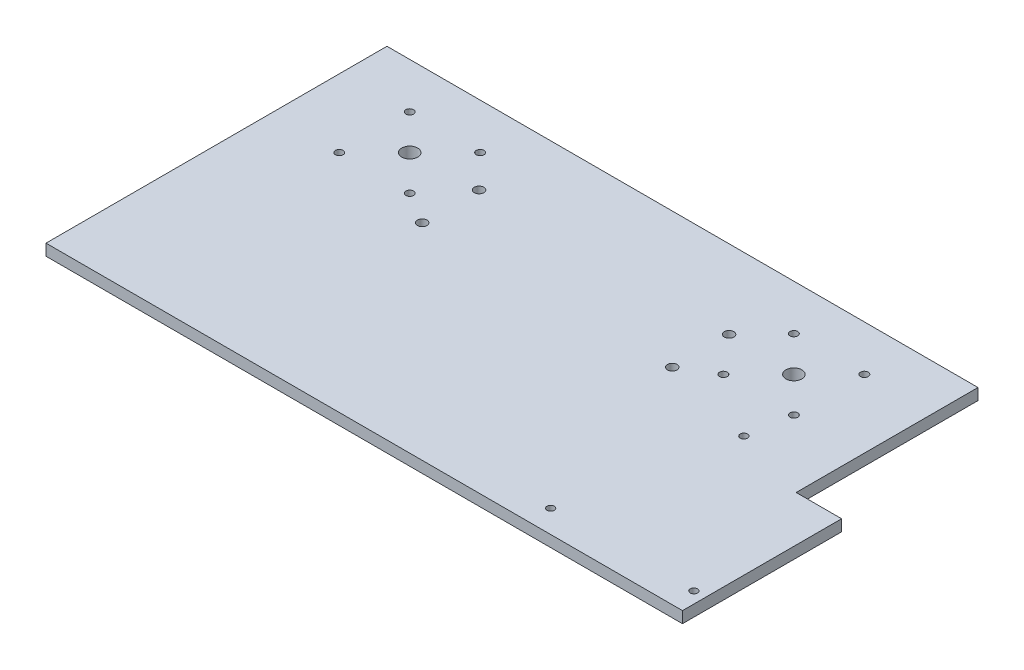
SolidWorks part; units mm, degrees
ref_plane "前视基准面" through (0, 0, 0) normal (0, 0, 1) x (1, 0, 0)
ref_plane "上视基准面" through (0, 0, 0) normal (0, 1, 0) x (1, 0, 0)
ref_plane "右视基准面" through (0, 0, 0) normal (1, 0, 0) x (0, 0, -1)
sketch "草图1" plane through (0, 0, 0) normal (0, 1, 0) x (1, 0, 0)
  line L1 (-140, -75) -> (140, -75)
  line L2 (-140, -75) -> (-140, 75)
  line L3 (-140, 75) -> (140, 75)
  line L4 (140, -75) -> (140, 75)
  line L5 (-140, -75) -> (140, 75) construction
  line L6 (-140, 75) -> (140, -75) construction
  line L7 (140, 75) -> (120, 75)
  line L8 (140, 75) -> (140, -5)
  line L9 (140, -5) -> (120, -5)
  line L10 (120, 75) -> (120, -5)
  line L11 (59, 24) -> (90, 24) construction
  line L12 (59, 24) -> (59, 55) construction
  line L13 (59, 55) -> (90, 55) construction
  line L14 (90, 24) -> (90, 55) construction
  line L15 (59, 24) -> (90, 55) construction
  line L16 (59, 55) -> (90, 24) construction
  line L17 (-110, 24) -> (-79, 24) construction
  line L18 (-110, 24) -> (-110, 55) construction
  line L19 (-110, 55) -> (-79, 55) construction
  line L20 (-79, 24) -> (-79, 55) construction
  line L21 (-110, 24) -> (-79, 55) construction
  line L22 (-110, 55) -> (-79, 24) construction
  line L24 (-65, 40.5) -> (45, 40.5) construction
  line L25 (-65, 40.5) -> (-65, 15.5) construction
  line L26 (-65, 15.5) -> (45, 15.5) construction
  line L27 (45, 40.5) -> (45, 15.5) construction
  circle A0 centre (59, 55) radius 1.7
  circle A1 centre (90, 55) radius 1.7
  circle A2 centre (59, 24) radius 1.7
  circle A3 centre (90, 24) radius 1.7
  circle A4 centre (-110, 55) radius 1.7
  circle A5 centre (-79, 55) radius 1.7
  circle A6 centre (-110, 24) radius 1.7
  circle A7 centre (-79, 24) radius 1.7
  circle A8 centre (-94.5, 39.5) radius 3.5
  circle A9 centre (74.5, 39.5) radius 3.5
  circle A10 centre (-65, 15.5) radius 2.1
  circle A11 centre (-65, 40.5) radius 2.1
  circle A12 centre (45, 15.5) radius 2.1
  circle A13 centre (45, 40.5) radius 2.1
  circle A17 centre (135, -65) radius 1.6
  circle A18 centre (87, 5) radius 1.6
  circle A19 centre (72, -65) radius 1.6
  point P0 (0, 0)
  point P9 (74.5, 39.5)
  dimension "D9" = 3.4
  dimension "D10" = 3.4
  dimension "D11" = 3.4
  dimension "D12" = 3.4
  dimension "D17" = 3.4
  dimension "D18" = 3.4
  dimension "D19" = 3.4
  dimension "D20" = 3.4
  dimension "D21" = 7
  dimension "D22" = 7
  dimension "D27" = 4.2
  dimension "D28" = 4.2
  dimension "D29" = 4.2
  dimension "D30" = 4.2
  dimension "D31" = 10
  dimension "D32" = 10
  dimension "D33" = 80
  dimension "D34" = 68
  dimension "D35" = 53
  dimension "D36" = 5
  dimension "D37" = 3.2
  dimension "D38" = 3.2
  dimension "D39" = 3.2
  dimension "D1" = 280
  dimension "D2" = 150
  dimension "D3" = 80
  dimension "D4" = 20
  dimension "D5" = 20
  dimension "D6" = 31
  dimension "D7" = 31
  dimension "D8" = 50
  dimension "D13" = 20
  dimension "D14" = 30
  dimension "D15" = 31
  dimension "D16" = 31
  dimension "D23" = 34.5
  dimension "D24" = 110
  dimension "D25" = 14
  dimension "D26" = 25
extrude "凸台-拉伸1" add sketch "草图1" along normal blind 5 contours L10 L3 L2 L1 L4 L9
